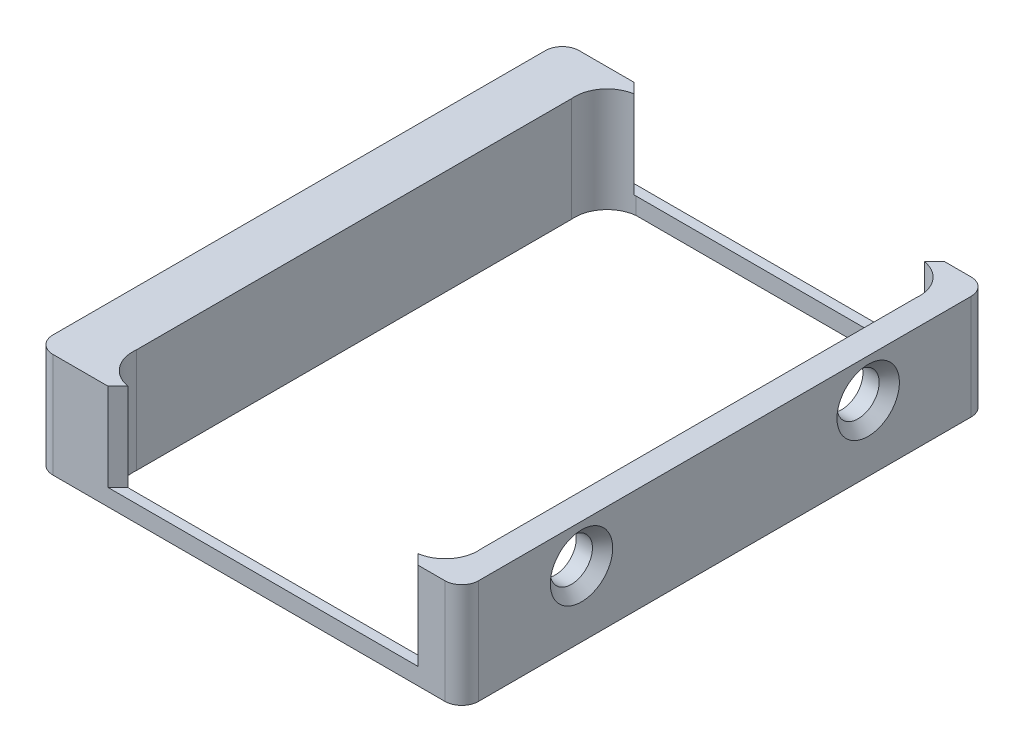
SolidWorks part; units mm, degrees
ref_plane "Front Plane" through (0, 0, 0) normal (0, 0, 1) x (1, 0, 0)
ref_plane "Top Plane" through (0, 0, 0) normal (0, 1, 0) x (1, 0, 0)
ref_plane "Right Plane" through (0, 0, 0) normal (1, 0, 0) x (0, 0, -1)
other "Configuration Table"
sketch "草图1" plane through (0, 0, 0) normal (0, 1, 0) x (1, 0, 0)
  line L0 (0, -75.1) -> (0, 75.1) construction
  line L1 (-51.1, 0) -> (51.1, 0) construction
  line L2 (-42.5, 75.1) -> (42.5, 75.1)
  line L3 (-51.1, -64.5) -> (-51.1, 64.5)
  line L4 (-42.5, -75.1) -> (42.5, -75.1)
  line L5 (51.1, -64.5) -> (51.1, 64.5)
  line L6 (-51.1, 0) -> (-67.3, 0) construction
  line L7 (-67.3, -78) -> (-67.3, 78)
  line L8 (51.1, 0) -> (58.9, 0) construction
  line L9 (58.9, -78) -> (58.9, 78)
  line L10 (-67.3, 78) -> (58.9, 78)
  line L11 (-67.3, -78) -> (58.9, -78)
  arc A4 (-51.1, 64.5) -> (-42.5, 75.1) centre (-41.5, 65.5) cw
  arc A5 (-51.1, -64.5) -> (-42.5, -75.1) centre (-41.5, -65.5) ccw
  arc A6 (42.5, -75.1) -> (51.1, -64.5) centre (41.5, -65.5) ccw
  arc A7 (42.5, 75.1) -> (51.1, 64.5) centre (41.5, 65.5) cw
  point P4 (0, 0)
  point P9 (0, 0)
  point P12 (0, 75.1)
  point P15 (-51.1, 0)
  point P27 (-67.3, 0)
  point P31 (58.9, 0)
  dimension "D1" = 16.2
  dimension "D4" = 85
  dimension "D2" = 51.1
  dimension "D3" = 7.8
  dimension "D5" = 129
extrude "凸台-拉伸1" add sketch "草图1" along normal blind 31 contours L11 L9 L10 L7
sketch "草图2" plane through (0, 31, 0) normal (0, 1, 0) x (1, 0, 0)
  line L0 (0, 0) -> (0, 78) construction
  line L1 (58.9, 78) -> (-67.3, 78) construction
  line L2 (-46, 78) -> (46, 78)
  line L3 (-43.1, 75.1) -> (43.1, 75.1)
  line L4 (-43.1, 75.1) -> (-42.7809, 74.7809)
  line L5 (42.5, 75.1) -> (-42.5, 75.1) construction
  line L6 (-43.1, 75.1) -> (-46, 78)
  line L7 (43.1, 75.1) -> (46, 78)
  line L8 (0, 0) -> (58.9, 0) construction
  line L9 (58.9, -78) -> (58.9, 78) construction
  line L14 (-42.7809, 74.7809) -> (-42.5, 75.1)
  line L15 (43.1, 75.1) -> (42.8724, 74.8724)
  line L16 (42.8724, 74.8724) -> (42.5, 75.1)
  line L17 (42.8724, -74.8724) -> (42.5, -75.1)
  line L18 (43.1, -75.1) -> (42.8724, -74.8724)
  line L19 (-42.7809, -74.7809) -> (-42.5, -75.1)
  line L20 (-43.1, -75.1) -> (-42.7809, -74.7809)
  line L21 (-43.1, -75.1) -> (43.1, -75.1)
  line L22 (-43.1, -75.1) -> (-46, -78)
  line L23 (-46, -78) -> (46, -78)
  line L24 (43.1, -75.1) -> (46, -78)
  point P8 (0, 78)
  point P14 (0, 75.1)
extrude "切除-拉伸1" cut sketch "草图2" against normal blind 26
fillet "圆角1" radius 5 4 edges at (-67.3, 15.5, -78) (58.9, 15.5, -78) (58.9, 15.5, 78) (-67.3, 15.5, 78)
sketch "草图5" plane through (58.9, 0, 0) normal (1, 0, 0) x (0, 0, -1)
  line L0 (-78, 0) -> (-78, 31) construction
  line L1 (-73, 0) -> (73, 0) construction
  line L2 (78, 31) -> (78, 0) construction
  point P0 (42.5, 19.55)
  point P2 (-42.5, 19.55)
  dimension "D1" = 35.5
  dimension "D2" = 19.55
  dimension "D3" = 35.5
  dimension "D4" = 19.55
hole_wizard "Ø12.0mm 暗销孔1" positions "草图5" profile "草图4" hole size "Ø12.0" standard "ANSI Metric"
sketch "草图4" plane through (58.9, 19.55, -42.5) normal (0, 1, 0) x (0, 0, -1)
  line L0 (0, 0) -> (0, 20.7554)
  line L1 (0, 20.7554) -> (6.25, 17)
  line L2 (6.25, 17) -> (6.25, 0)
  line L5 (6.25, 0) -> (0, 0)
  line L10 (0, 20.7554) -> (-6.25, 17) construction
  line L11 (0, -6.35) -> (0, 107.95) construction
  dimension "孔直径" = 12.5
  dimension "孔深度" = 17
  dimension "导头角度" = 118
sketch "草图6" plane through (-67.3, 0, 0) normal (-1, 0, 0) x (0, 0, 1)
  line L0 (0, 0) -> (0, 13.95) construction
  line L1 (0, 13.95) -> (-11, 13.95) construction
  circle A2 centre (-11, 13.95) radius 2.1
  circle A3 centre (11, 13.95) radius 2.1
  point P4 (0, 13.45)
  dimension "D1" = 4.2
extrude "切除-拉伸2" cut sketch "草图6" against normal blind 10
sketch "草图7" plane through (0, 0, 0) normal (0, -1, 0) x (1, 0, 0)
  circle A0 centre (-58.4934, 70.9643) radius 2.1
  circle A1 centre (53.705, 73.3482) radius 2.1
  circle A2 centre (-58.4934, -70.9643) radius 2.1
  circle A3 centre (53.705, -73.3482) radius 2.1
extrude "切除-拉伸3" cut sketch "草图7" against normal blind 10
chamfer "倒角1" distance 3 angle 45 2 edges at (58.9, 19.55, 36.25) (58.9, 19.55, -48.75)
